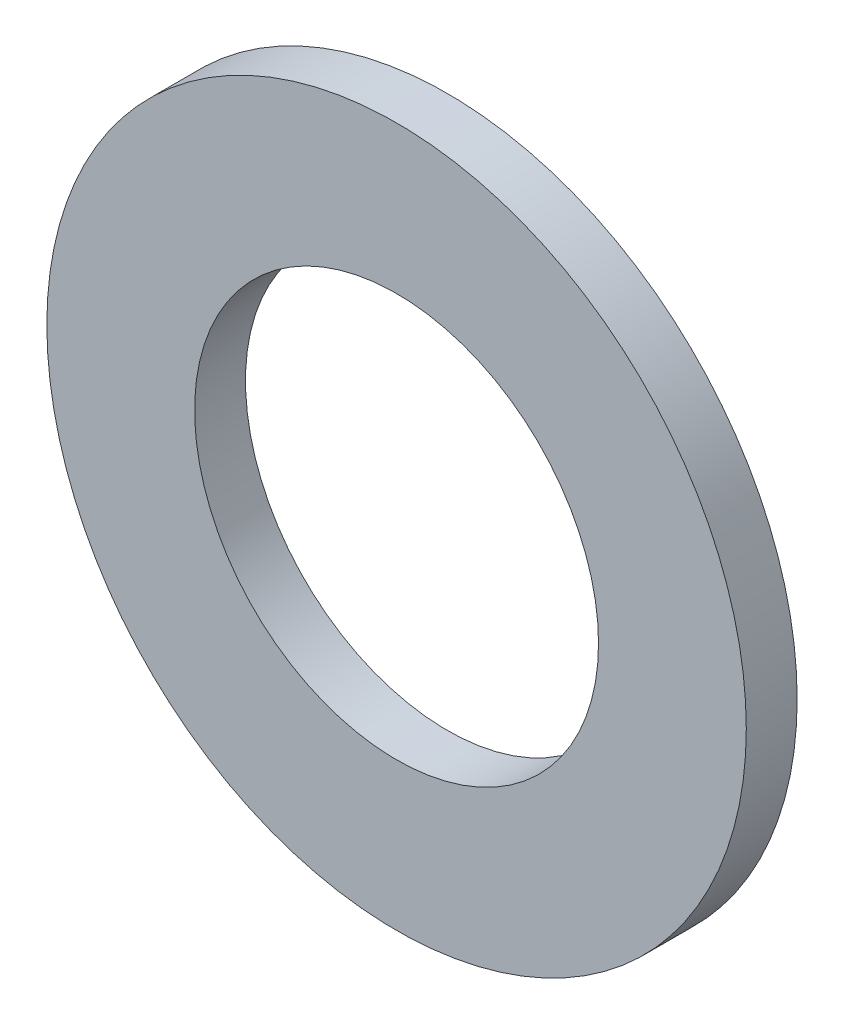
SolidWorks part; units mm, degrees
material "Nylon 6/10"
ref_plane "Front Plane" through (0, 0, 0) normal (0, 0, 1) x (1, 0, 0)
ref_plane "Top Plane" through (0, 0, 0) normal (0, 1, 0) x (1, 0, 0)
ref_plane "Right Plane" through (0, 0, 0) normal (1, 0, 0) x (0, 0, -1)
sketch "Sketch1" plane through (0, 0, 0) normal (0, 0, 1) x (1, 0, 0)
  circle A0 centre (0, 0) radius 4.3656
  circle A1 centre (0, 0) radius 8.7312
  dimension "ID" = 8.7312
  dimension "OD" = 17.4625
extrude "Extrude1" add sketch "Sketch1" against normal blind 1.27
hole_wizard "X (0.397) Diameter Hole1" positions "Sketch3" profile "Sketch2" hole size "X" standard "ANSI Inch"
sketch "Sketch3" plane through (0, 0, 0) normal (0, 0, 1) x (1, 0, 0)
  point P0 (0, 0)
sketch "Sketch2" plane through (0, 0, 0) normal (1, 0, 0) x (0, -1, 0)
  line L0 (0, 0) -> (0, 15.7295)
  line L1 (0, 15.7295) -> (5.0419, 12.7)
  line L2 (5.0419, 12.7) -> (5.0419, 0)
  line L5 (5.0419, 0) -> (0, 0)
  line L10 (0, 15.7295) -> (-5.0419, 12.7) construction
  line L11 (0, -6.35) -> (0, 107.95) construction
  dimension "Hole Dia." = 10.0838
  dimension "Hole Depth" = 12.7
  dimension "Drill Angle" = 118
